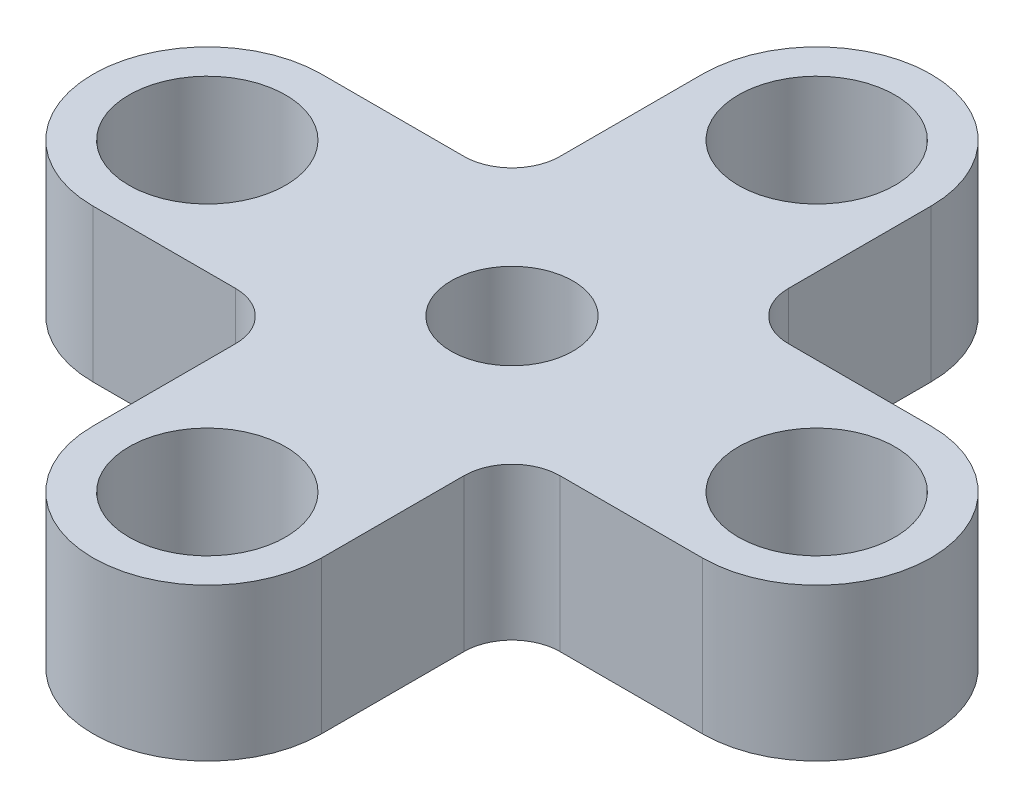
SolidWorks part; units mm, degrees
material "6061 Alloy"
ref_plane "Front Plane" through (0, 0, 0) normal (0, 0, 1) x (1, 0, 0)
ref_plane "Top Plane" through (0, 0, 0) normal (0, 1, 0) x (1, 0, 0)
ref_plane "Right Plane" through (0, 0, 0) normal (1, 0, 0) x (0, 0, -1)
sketch "Sketch1" plane through (0, 0, 0) normal (0, 1, 0) x (1, 0, 0)
  line L0 (-5.1918, 13) -> (5.1918, 13)
  line L1 (5.9213, 11.3161) -> (0.7295, 5.7782)
  line L2 (-0.7295, 5.7782) -> (-5.9213, 11.3161)
  line L3 (-19.7185, 12.4972) -> (-22.78, 5.1062)
  line L4 (-21.6079, 3.7548) -> (-15.1498, 5.4093)
  line L5 (-14.5375, 6.8876) -> (-17.9341, 12.624)
  line L6 (-21.2492, 8.8017) -> (-13.8582, 5.7403) construction
  line L7 (-13.8582, 5.7403) -> (0, 0) construction
  line L8 (0, 5) -> (0, 13) construction
  line L9 (0, 0) -> (-9.4361, 0) construction
  circle A0 centre (0, 0) radius 25.4
  circle A1 centre (0, 0) radius 2.54
  circle A2 centre (0, 12.7) radius 3.2639
  circle A3 centre (0, 0) radius 25.4
  circle A4 centre (12.7, 0) radius 3.2639
  circle A5 centre (0, 0) radius 25.4
  circle A6 centre (0, -12.7) radius 3.2639
  circle A7 centre (0, 0) radius 25.4
  circle A8 centre (-12.7, 0) radius 3.2639
  arc A9 (0.7295, 5.7782) -> (-0.7295, 5.7782) centre (0, 6.4621) cw
  arc A10 (5.1918, 13) -> (5.9213, 11.3161) centre (5.1918, 12) cw
  arc A11 (-5.1918, 13) -> (-5.9213, 11.3161) centre (-5.1918, 12) ccw
  arc A12 (-22.78, 5.1062) -> (-21.6079, 3.7548) centre (-21.8561, 4.7235) ccw
  arc A13 (-15.1498, 5.4093) -> (-14.5375, 6.8876) centre (-15.398, 6.3781) ccw
  arc A14 (-19.7185, 12.4972) -> (-17.9341, 12.624) centre (-18.7946, 12.1146) cw
  point P8 (0, 13)
  point P18 (0, 0)
  point P31 (7.5, 13)
  point P34 (-7.5, 13)
  point P52 (0, 0)
  dimension "D1" = 5.08
  dimension "D2" = 50.8
  dimension "D3" = 6.5278
  dimension "D11" = 1
  dimension "D4" = 12.7
  dimension "D6" = 5
  dimension "D7" = 8
  dimension "D8" = 15
  dimension "D9" = 22.5
  dimension "D10" = 15
  dimension "D12" = 8
  dimension "D5" = 4
extrude "Boss-Extrude1" add sketch "Sketch1" along normal blind 6.35 contours A0 A8 A6 A4 A2 A1 | A14 L3 A12 L4 A13 L5 | L0 A11 L2 A9 L1 A10
sketch "Sketch2" plane through (0, 0, 0) normal (0, 1, 0) x (1, 0, 0)
  line L0 (4.7625, 12.7) -> (4.7625, 6.7625)
  line L1 (6.7625, 4.7625) -> (12.7, 4.7625)
  line L2 (12.7, -4.7625) -> (6.7625, -4.7625)
  line L3 (4.7625, -6.7625) -> (4.7625, -12.7)
  line L4 (-4.7625, 12.7) -> (-4.7625, 6.7625)
  line L5 (-6.7625, 4.7625) -> (-12.7, 4.7625)
  line L6 (-12.7, -4.7625) -> (-6.7625, -4.7625)
  line L7 (-4.7625, -6.7625) -> (-4.7625, -12.7)
  circle A0 centre (0, 12.7) radius 4.7625
  circle A1 centre (12.7, 0) radius 4.7625
  circle A2 centre (-12.7, 0) radius 4.7625
  circle A3 centre (0, -12.7) radius 4.7625
  circle A8 centre (0, 12.7) radius 3.2639 construction
  circle A9 centre (0, -12.7) radius 3.2639 construction
  circle A10 centre (-12.7, 0) radius 3.2639 construction
  circle A11 centre (12.7, 0) radius 3.2639 construction
  circle A12 centre (0, 0) radius 25.4
  circle A13 centre (0, 0) radius 25.4 construction
  arc A14 (6.7625, -4.7625) -> (4.7625, -6.7625) centre (6.7625, -6.7625) ccw
  arc A15 (-6.7625, -4.7625) -> (-4.7625, -6.7625) centre (-6.7625, -6.7625) cw
  arc A16 (-4.7625, 6.7625) -> (-6.7625, 4.7625) centre (-6.7625, 6.7625) cw
  arc A17 (4.7625, 6.7625) -> (6.7625, 4.7625) centre (6.7625, 6.7625) ccw
  point P35 (4.7625, -4.7625)
  dimension "D1" = 9.525
  dimension "D2" = 2
  dimension "D7" = 9.525
extrude "Cut-Extrude1" cut sketch "Sketch2" along normal blind 10 contours A12 A3 L7 L6 A2 L5 L4 A0 L0 L1 A1 L2 L3
